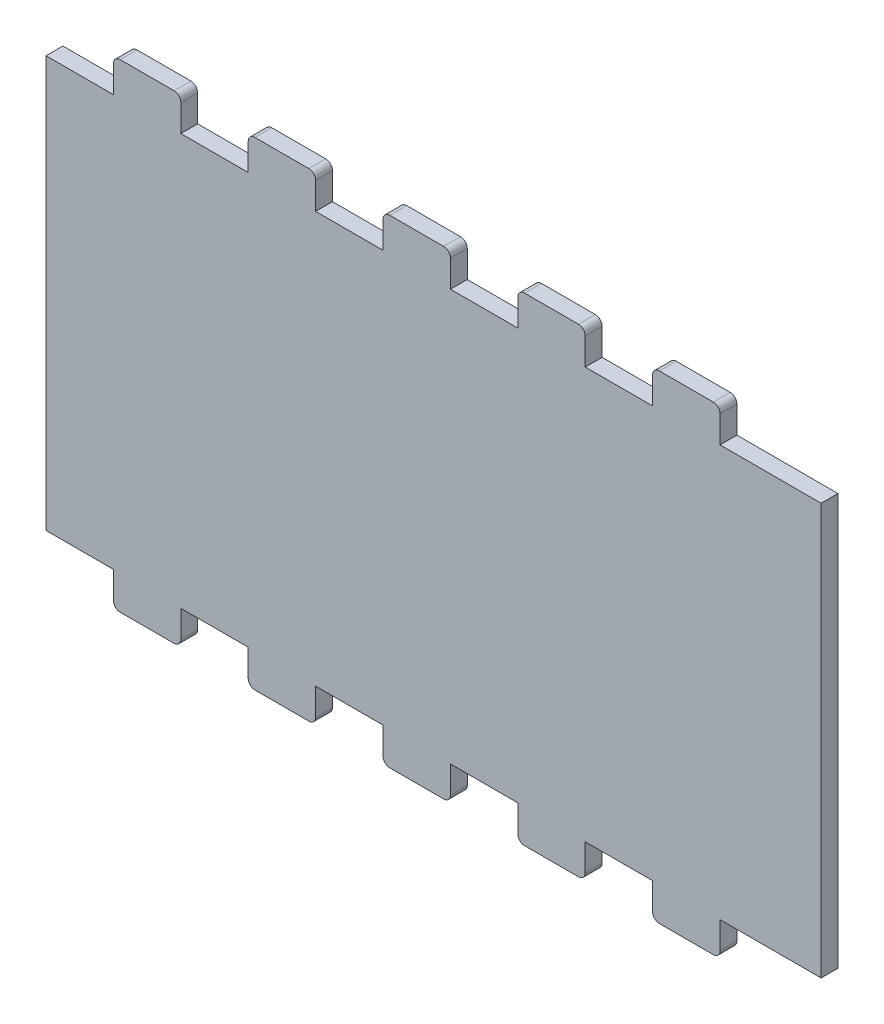
SolidWorks part; units mm, degrees
ref_plane "Front" through (0, 0, 0) normal (0, 0, 1) x (1, 0, 0)
ref_plane "Top" through (0, 0, 0) normal (0, 1, 0) x (1, 0, 0)
ref_plane "Right" through (0, 0, 0) normal (1, 0, 0) x (0, 0, -1)
sketch "Sketch1" plane through (0, 0, 0) normal (0, 0, 1) x (1, 0, 0)
  line L1 (0, 0) -> (230, 0)
  line L2 (0, 0) -> (0, 122)
  line L3 (0, 122) -> (230, 122)
  line L4 (230, 0) -> (230, 122)
  dimension "D1" = 122
  dimension "D2" = 230
extrude "Boss-Extrude1" add sketch "Sketch1" along normal blind 5
sketch "Sketch2" plane through (0, 0, 5) normal (0, 0, 1) x (1, 0, 0)
  line L0 (230, 122) -> (0, 122) construction
  line L1 (20, 122) -> (40, 122)
  line L2 (20, 122) -> (20, 132)
  line L3 (20, 132) -> (40, 132)
  line L4 (40, 122) -> (40, 132)
  line L5 (0, 122) -> (0, 0) construction
  line L6 (60, 122) -> (60, 132)
  line L7 (60, 122) -> (80, 122)
  line L8 (80, 122) -> (80, 132)
  line L9 (60, 132) -> (80, 132)
  line L10 (100, 122) -> (100, 132)
  line L11 (100, 122) -> (120, 122)
  line L12 (120, 122) -> (120, 132)
  line L13 (100, 132) -> (120, 132)
  line L14 (140, 122) -> (140, 132)
  line L15 (140, 122) -> (160, 122)
  line L16 (160, 122) -> (160, 132)
  line L17 (140, 132) -> (160, 132)
  line L18 (180, 122) -> (180, 132)
  line L19 (180, 122) -> (200, 122)
  line L20 (200, 122) -> (200, 132)
  line L21 (180, 132) -> (200, 132)
  dimension "D1" = 20
  dimension "D2" = 10
  dimension "D3" = 20
  dimension "D4" = 5
extrude "Boss-Extrude2" add sketch "Sketch2" against normal up to surface (5 mm away) up to face at (115, 61, 0)
ref_plane "Plane1" through (0, 61, 0) normal (0, 1, 0) x (1, 0, 0)
fillet "Fillet1" radius 2 10 edges at (200, 132, 2.5) (180, 132, 2.5) (140, 132, 2.5) (160, 132, 2.5) (120, 132, 2.5) (100, 132, 2.5) (80, 132, 2.5) (60, 132, 2.5) (40, 132, 2.5) (20, 132, 2.5)
mirror "Mirror1" about plane through (0, 61, 0) normal (0, 1, 0) of "Fillet1", "Boss-Extrude2"
